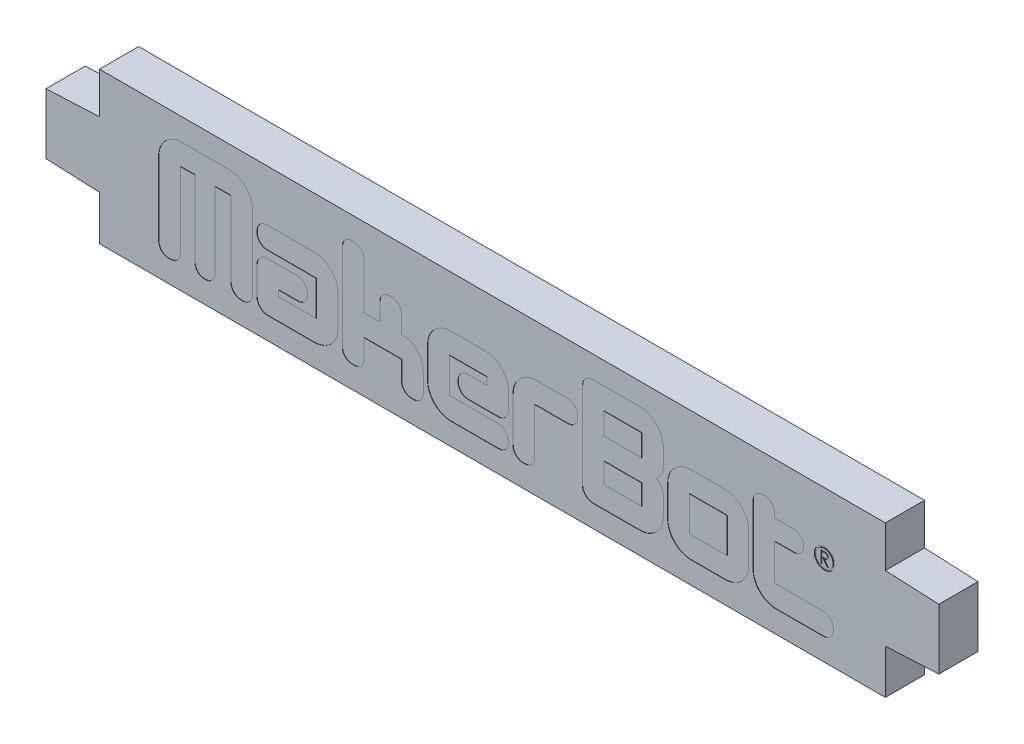
SolidWorks part; units mm, degrees
ref_plane "Front Plane" through (0, 0, 0) normal (0, 0, 1) x (1, 0, 0)
ref_plane "Top Plane" through (0, 0, 0) normal (0, 1, 0) x (1, 0, 0)
ref_plane "Right Plane" through (0, 0, 0) normal (1, 0, 0) x (0, 0, -1)
sketch "Sketch1" plane through (0, 0, 0) normal (0, 0, 1) x (1, 0, 0)
  line L0 (63.3173, 2.0893) -> (-65.1827, 2.0893)
  line L1 (-73.9327, 14.7145) -> (72.0673, 14.7145) construction
  line L2 (-73.9327, 9.7645) -> (-65.1827, 9.3645)
  line L3 (-65.1827, 20.0645) -> (-65.1827, 9.3645) construction
  line L4 (63.3173, 20.0645) -> (63.3173, 26.8097)
  line L5 (63.3173, 9.3645) -> (63.3173, 2.0893)
  line L6 (72.0673, 19.6645) -> (63.3173, 20.0645)
  line L7 (72.0673, 19.6645) -> (72.0673, 9.7645)
  line L8 (72.0673, 9.7645) -> (63.3173, 9.3645)
  line L10 (-65.1827, 26.8097) -> (63.3173, 26.8097)
  line L24 (-73.9327, 19.6645) -> (-73.9327, 9.7645)
  line L25 (-73.9327, 19.6645) -> (-65.1827, 20.0645)
  line L26 (-65.1827, 9.3645) -> (-65.1827, 2.0893)
  line L27 (-65.1827, 20.0645) -> (-65.1827, 26.8097)
  dimension "D1" = 9.9
  dimension "D2" = 10.7
  dimension "D3" = 10.7
extrude "Boss-Extrude1" add sketch "Sketch1" along normal blind 6.4
sketch "Sketch5" plane through (0, 0, 6.4) normal (0, 0, 1) x (1, 0, 0)
  text T0 "MakerBot" font "Designer Block" height 17.5
extrude "Cut-Extrude3" cut sketch "Sketch5" against normal blind 0.05
sketch "Sketch11" plane through (0, 0, 6.4) normal (0, 0, 1) x (1, 0, 0)
  circle A0 centre (53.3574, 16.7868) radius 1.405
  circle A1 centre (53.3574, 16.7868) radius 1.655
  dimension "D1" = 2.81
  dimension "D2" = 3.31
extrude "Cut-Extrude6" cut sketch "Sketch11" against normal blind 0.1
sketch "Sketch12" plane through (0, 0, 6.4) normal (0, 0, 1) x (1, 0, 0)
  text T0 "R" font "Century Gothic" height 2
extrude "Cut-Extrude7" cut sketch "Sketch12" against normal blind 0.1
